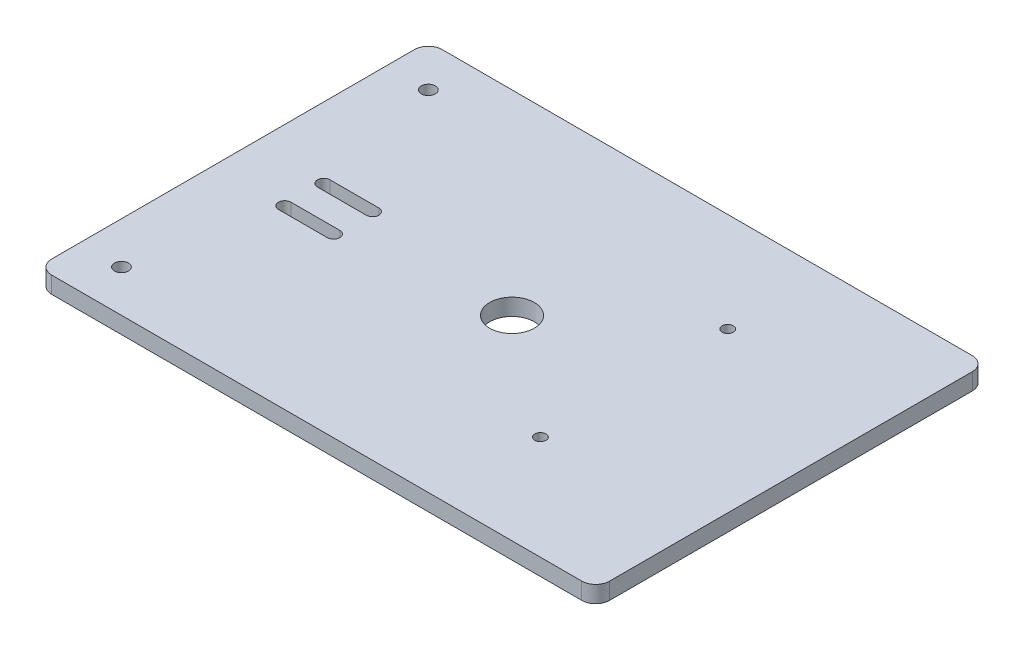
SolidWorks part; units mm, degrees
material "ABS"
ref_plane "Front Plane" through (0, 0, 0) normal (0, 0, 1) x (1, 0, 0)
ref_plane "Top Plane" through (0, 0, 0) normal (0, 1, 0) x (1, 0, 0)
ref_plane "Right Plane" through (0, 0, 0) normal (1, 0, 0) x (0, 0, -1)
sketch "Sketch2" plane through (0, 0, 0) normal (0, 1, 0) x (1, 0, 0)
  line L1 (-100, 70) -> (100, 70)
  line L2 (-100, 70) -> (-100, -70)
  line L3 (-100, -70) -> (100, -70)
  line L4 (100, 70) -> (100, -70)
  line L5 (-100, 70) -> (100, -70) construction
  line L6 (-100, -70) -> (100, 70) construction
  point P0 (0, 0)
  dimension "D1" = 200
  dimension "D2" = 140
extrude "Boss-Extrude1" add sketch "Sketch2" along normal blind 6
fillet "Fillet1" radius 5 4 edges at (-100, 3, -70) (-100, 3, 70) (100, 3, -70) (100, 3, 70)
sketch "Sketch3" plane through (0, 6, 0) normal (0, 1, 0) x (1, 0, 0)
  line L0 (-100, 65) -> (-100, -65) construction
  line L1 (95, 70) -> (-95, 70) construction
  circle A0 centre (-85, 55) radius 2.5
  circle A1 centre (-85, -55) radius 2.5
  dimension "D1" = 5
  dimension "D2" = 15
  dimension "D3" = 15
extrude "Cut-Extrude1" cut sketch "Sketch3" against normal through all
sketch "Sketch4" plane through (0, 6, 0) normal (0, 1, 0) x (1, 0, 0)
  circle A0 centre (0, 0) radius 8
  dimension "D1" = 16
extrude "Cut-Extrude2" cut sketch "Sketch4" against normal through all
sketch "Sketch5" plane through (0, 6, 0) normal (0, 1, 0) x (1, 0, 0)
  line L5 (-16, 16) -> (16, -16) construction
  line L6 (-16, -16) -> (16, 16) construction
  circle A2 centre (16, 16) radius 2
  circle A3 centre (16, -16) radius 2
  circle A4 centre (-16, -16) radius 2
  circle A5 centre (-16, 16) radius 2
  point P0 (0, 0)
  dimension "D1" = 32
  dimension "D2" = 32
  dimension "D3" = 4
  dimension "D4" = 4
  dimension "D5" = 4
  dimension "D6" = 4
  dimension "D7" = 16
  dimension "D8" = 16
sketch "Sketch6" plane through (0, 6, 0) normal (0, 1, 0) x (1, 0, 0)
  line L0 (-74.6884, 7.2137) -> (-57.1884, 7.2137) construction
  line L1 (-74.6884, 9.4637) -> (-57.1884, 9.4637)
  line L2 (-74.6884, 4.9637) -> (-57.1884, 4.9637)
  line L3 (-74.7477, -6.7369) -> (-57.2477, -6.7369) construction
  line L4 (-74.7477, -4.4869) -> (-57.2477, -4.4869)
  line L5 (-74.7477, -8.9869) -> (-57.2477, -8.9869)
  arc A0 (-74.6884, 9.4637) -> (-74.6884, 4.9637) centre (-74.6884, 7.2137) ccw
  arc A1 (-57.1884, 4.9637) -> (-57.1884, 9.4637) centre (-57.1884, 7.2137) ccw
  arc A2 (-74.7477, -4.4869) -> (-74.7477, -8.9869) centre (-74.7477, -6.7369) ccw
  arc A3 (-57.2477, -8.9869) -> (-57.2477, -4.4869) centre (-57.2477, -6.7369) ccw
  point P2 (-65.9384, 7.2137)
  point P10 (-65.9977, -6.7369)
  point P15 (-65, 25)
  point P16 (-76.9384, 7.2137)
  point P17 (-54.9384, 7.2137)
  point P18 (-76.9977, -6.7369)
  point P19 (-54.9977, -6.7369)
  dimension "D1" = 22
  dimension "D2" = 4.5
  dimension "D3" = 22
extrude "Cut-Extrude4" cut sketch "Sketch6" against normal through all
sketch "Sketch7" plane through (0, 6, 0) normal (0, 1, 0) x (1, 0, 0)
  circle A0 centre (42.9027, -32.7205) radius 2
  circle A1 centre (42.9027, 34.4183) radius 2
  point P0 (42.9027, -32.7205)
  dimension "D4" = 4
  dimension "D5" = 4
extrude "Cut-Extrude5" cut sketch "Sketch7" against normal through all
